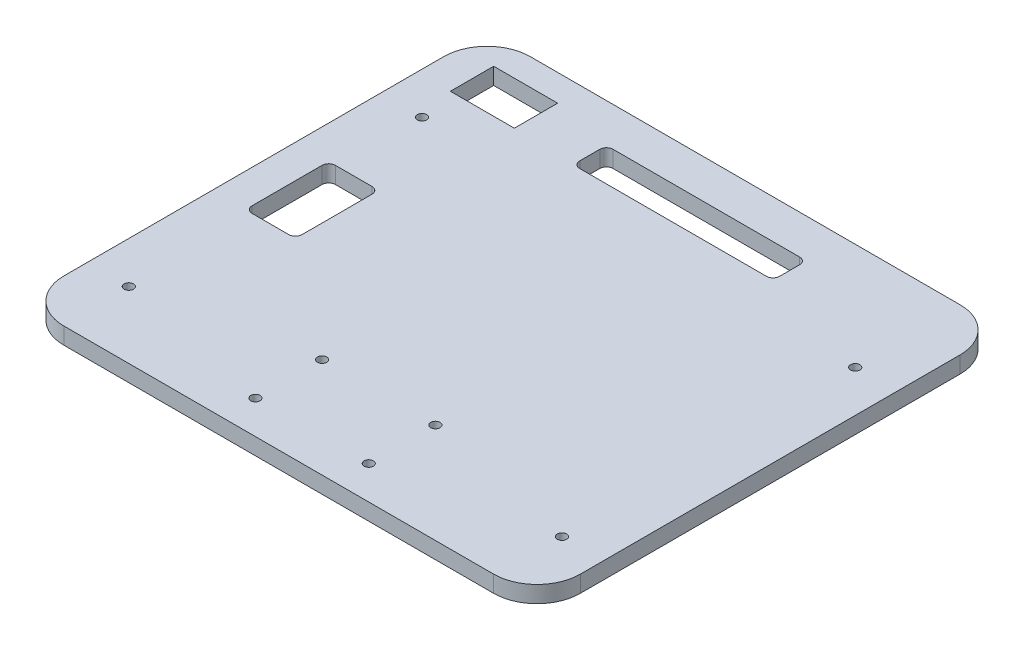
SolidWorks part; units mm, degrees
ref_plane "Front Plane" through (0, 0, 0) normal (0, 0, 1) x (1, 0, 0)
ref_plane "Top Plane" through (0, 0, 0) normal (0, 1, 0) x (1, 0, 0)
ref_plane "Right Plane" through (0, 0, 0) normal (1, 0, 0) x (0, 0, -1)
sketch "Sketch1" plane through (0, 0, 0) normal (0, 1, 0) x (1, 0, 0)
  line L1 (77.5, -70) -> (-77.5, -70)
  line L2 (77.5, -70) -> (77.5, 70)
  line L3 (77.5, 70) -> (-77.5, 70)
  line L4 (-77.5, -70) -> (-77.5, 70)
  line L5 (77.5, -70) -> (-77.5, 70) construction
  line L6 (77.5, 70) -> (-77.5, -70) construction
  point P0 (0, 0)
  dimension "D1" = 155
  dimension "D2" = 140
extrude "Boss-Extrude1" add sketch "Sketch1" along normal blind 5
sketch "Sketch2" plane through (0, 5, 0) normal (0, 1, 0) x (1, 0, 0)
  line L1 (-77.5, 70) -> (-77.5, -70) construction
  line L4 (77.5, 70) -> (-77.5, 70) construction
  line L6 (-77.5, 70) -> (-77.5, 57)
  line L7 (-77.5, 70) -> (-64.5, 70)
  line L8 (77.5, 70) -> (64.5, 70)
  line L9 (77.5, 70) -> (77.5, 57)
  line L10 (77.5, -70) -> (77.5, -57)
  line L11 (77.5, -70) -> (64.5, -70)
  line L12 (-77.5, -70) -> (-64.5, -70)
  line L13 (-77.5, -70) -> (-77.5, -57)
  arc A0 (-77.5, 57) -> (-64.5, 70) centre (-64.5, 57) cw
  arc A1 (77.5, 57) -> (64.5, 70) centre (64.5, 57) ccw
  arc A2 (77.5, -57) -> (64.5, -70) centre (64.5, -57) cw
  arc A3 (-77.5, -57) -> (-64.5, -70) centre (-64.5, -57) ccw
  dimension "D1" = 13
  dimension "D2" = 13
extrude "Cut-Extrude1" cut sketch "Sketch2" against normal blind 5
sketch "Sketch3" plane through (0, 5, 0) normal (0, 1, 0) x (1, 0, 0)
  circle A0 centre (-65, 38) radius 1.4
  circle A1 centre (65, 38) radius 1.4
  circle A2 centre (65, -50) radius 1.4
  circle A3 centre (-65, -50) radius 1.4
  dimension "D1" = 130
  dimension "D2" = 20
  dimension "D3" = 20
  dimension "D4" = 88
  dimension "D5" = 130
extrude "Cut-Extrude2" cut sketch "Sketch3" against normal blind 5
sketch "Sketch5" plane through (0, 5, 0) normal (0, 1, 0) x (1, 0, 0)
  line L1 (-30, 58.3356) -> (30, 58.3356)
  line L2 (-30, 58.3356) -> (-30, 48.3356)
  line L3 (-30, 48.3356) -> (30, 48.3356)
  line L4 (30, 58.3356) -> (30, 48.3356)
  line L5 (-30, 58.3356) -> (30, 48.3356) construction
  line L6 (-30, 48.3356) -> (30, 58.3356) construction
  point P0 (0, 53.3356)
  dimension "D1" = 10
  dimension "D2" = 60
extrude "Cut-Extrude3" cut sketch "Sketch5" against normal blind 5
sketch "Sketch6" plane through (0, 5, 0) normal (0, 1, 0) x (1, 0, 0)
  line L1 (-64.5, -70) -> (64.5, -70) construction
  circle A0 centre (-17, -40) radius 1.4
  circle A1 centre (17, -40) radius 1.4
  circle A2 centre (17, -60) radius 1.4
  circle A3 centre (-17, -60) radius 1.4
  dimension "D1" = 30
  dimension "D2" = 34
extrude "Cut-Extrude4" cut sketch "Sketch6" against normal blind 10
sketch "Sketch7" plane through (0, 5, 0) normal (0, 1, 0) x (1, 0, 0)
  line L0 (-77.5, 57) -> (-77.5, -57) construction
  line L1 (-67.5, 12.5) -> (-52.5, 12.5)
  line L2 (-67.5, 12.5) -> (-67.5, -12.5)
  line L3 (-67.5, -12.5) -> (-52.5, -12.5)
  line L4 (-52.5, 12.5) -> (-52.5, -12.5)
  line L5 (-67.5, 12.5) -> (-52.5, -12.5) construction
  line L6 (-67.5, -12.5) -> (-52.5, 12.5) construction
  point P0 (-60, 0)
  dimension "D1" = 10
  dimension "D2" = 0
  dimension "D3" = 25
  dimension "D4" = 15
extrude "Cut-Extrude5" cut sketch "Sketch7" against normal blind 10
sketch "Sketch8" plane through (0, 5, 0) normal (0, 1, 0) x (1, 0, 0)
  line L1 (-67.5, 62) -> (-48.3, 62)
  line L2 (-67.5, 62) -> (-67.5, 49)
  line L3 (-67.5, 49) -> (-48.3, 49)
  line L4 (-48.3, 62) -> (-48.3, 49)
  line L5 (-67.5, 62) -> (-48.3, 49) construction
  line L6 (-67.5, 49) -> (-48.3, 62) construction
  point P0 (-57.9, 55.5)
  dimension "D1" = 19.2
  dimension "D2" = 13
extrude "Cut-Extrude6" cut sketch "Sketch8" against normal blind 10
fillet "Fillet2" radius 2 4 edges at (-52.5, 2.5, 12.5) (-67.5, 2.5, 12.5) (-52.5, 2.5, -12.5) (-67.5, 2.5, -12.5)
fillet "Fillet3" radius 2 4 edges at (30, 2.5, -48.3356) (-30, 2.5, -48.3356) (30, 2.5, -58.3356) (-30, 2.5, -58.3356)
